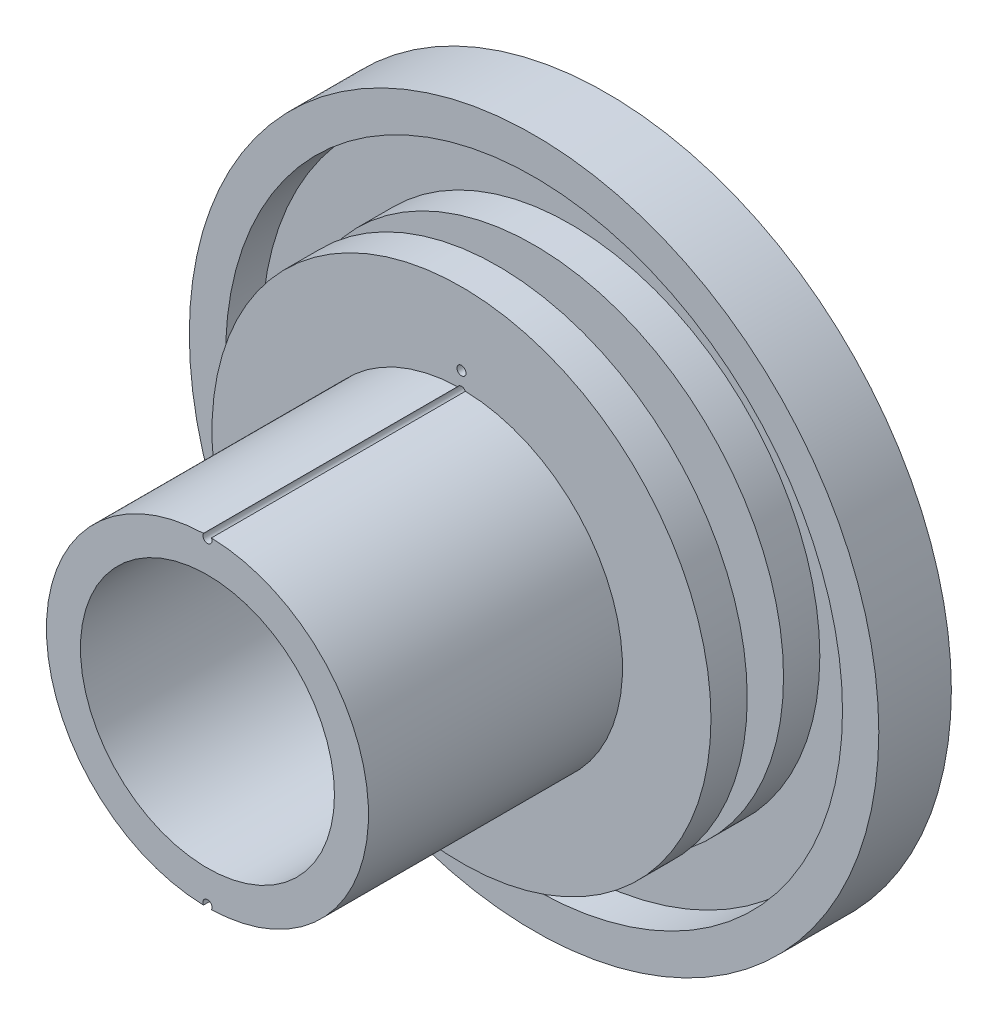
SolidWorks part; units mm, degrees
material "ABS"
ref_plane "Front Plane" through (0, 0, 0) normal (0, 0, 1) x (1, 0, 0)
ref_plane "Top Plane" through (0, 0, 0) normal (0, 1, 0) x (1, 0, 0)
ref_plane "Right Plane" through (0, 0, 0) normal (1, 0, 0) x (0, 0, -1)
sketch "Sketch1" plane through (0, 0, 0) normal (0, 0, 1) x (1, 0, 0)
  circle A0 centre (0, 0) radius 13.75
  dimension "D1" = 27.5
extrude "Boss-Extrude1" add sketch "Sketch1" along normal blind 2
sketch "Sketch2" plane through (0, 0, 0) normal (0, 0, 1) x (1, 0, 0)
  circle A0 centre (0, 0) radius 8.5
  dimension "D1" = 17
extrude "Boss-Extrude2" add sketch "Sketch2" along normal blind 6
sketch "Sketch3" plane through (0, 0, 0) normal (0, 0, 1) x (1, 0, 0)
  circle A0 centre (0, 0) radius 13.75
  dimension "D1" = 27.5
extrude "Boss-Extrude3" add sketch "Sketch3" along normal blind 2 from offset 4
sketch "Sketch5" plane through (0, 0, 0) normal (0, 0, 1) x (1, 0, 0)
  circle A0 centre (0, 0) radius 7
extrude "Cut-Extrude2" cut sketch "Sketch5" along normal mid plane 75
sketch "Sketch6" plane through (0, 0, 0) normal (0, 0, 1) x (1, 0, 0)
  circle A0 centre (0, 0) radius 7
  circle A1 centre (0, 0) radius 8.875
  dimension "D1" = 17.75
extrude "Boss-Extrude4" add sketch "Sketch6" along normal blind 14 from surface at 6 starting at face at (13.75, 0, 6)
sketch "Sketch9" plane through (0, 0, 0) normal (0, 0, 1) x (1, 0, 0)
  circle A0 centre (0, 9.75) radius 0.25
  circle A1 centre (0, -9.75) radius 0.25
  circle A2 centre (0, 8.75) radius 0.25
  circle A3 centre (0, -8.75) radius 0.25
extrude "Cut-Extrude3" cut sketch "Sketch9" along normal through all from surface at 4 starting at face at (13.75, 0, 4)
sketch "Sketch10" plane through (0, 0, 0) normal (0, 0, 1) x (1, 0, 0)
  circle A0 centre (0, 0) radius 19
  dimension "D1" = 38
extrude "Boss-Extrude5" add sketch "Sketch10" against normal blind 2
sketch "Sketch11" plane through (0, 0, 0) normal (0, 0, 1) x (1, 0, 0)
  circle A0 centre (0, 0) radius 7
  dimension "D1" = 14
extrude "Cut-Extrude4" cut sketch "Sketch11" against normal blind 2
sketch "Sketch12" plane through (0, 0, 0) normal (0, 0, 1) x (1, 0, 0)
  circle A1 centre (0, 0) radius 19
  circle A2 centre (0, 0) radius 17
  circle A3 centre (0, 0) radius 17
  dimension "D2" = 38
  dimension "D1" = 2
extrude "Boss-Extrude6" add sketch "Sketch12" along normal blind 2
